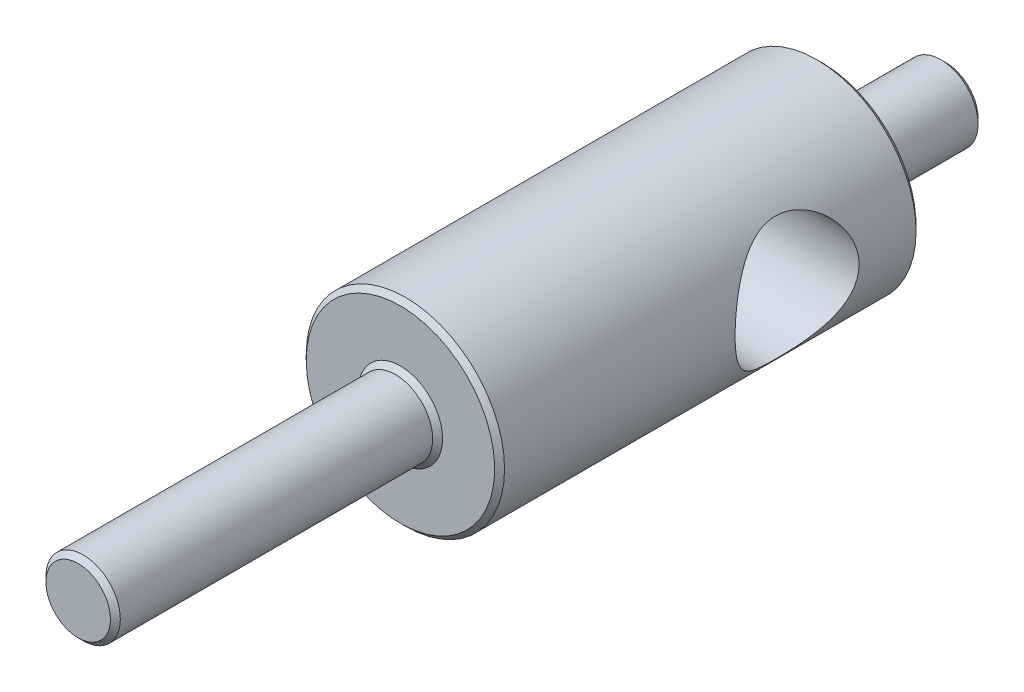
SolidWorks part; units mm, degrees
ref_plane "Front Plane" through (0, 0, 0) normal (0, 0, 1) x (1, 0, 0)
ref_plane "Top Plane" through (0, 0, 0) normal (0, 1, 0) x (1, 0, 0)
ref_plane "Right Plane" through (0, 0, 0) normal (1, 0, 0) x (0, 0, -1)
sketch "Sketch1" plane through (0, 0, 0) normal (0, 0, 1) x (1, 0, 0)
  circle A0 centre (0, 0) radius 1.5
  dimension "D1" = 3
extrude "Boss-Extrude1" add sketch "Sketch1" against normal blind 13
sketch "Sketch2" plane through (0, 0, -13) normal (0, 0, -1) x (-1, 0, 0)
  circle A0 centre (0, 0) radius 4
  dimension "D1" = 8
extrude "Boss-Extrude2" add sketch "Sketch2" along normal blind 17
sketch "Sketch3" plane through (0, 0, -30) normal (0, 0, -1) x (-1, 0, 0)
  circle A0 centre (0, 0) radius 1.5
  dimension "D1" = 3
extrude "Boss-Extrude3" add sketch "Sketch3" along normal blind 5
sketch "Sketch4" plane through (0, 0, 0) normal (1, 0, 0) x (0, 0, -1)
  line L0 (30, -4) -> (30, 4) construction
  circle A0 centre (25, 0) radius 2.5
  dimension "D1" = 5
  dimension "D2" = 5
extrude "Cut-Extrude1" cut sketch "Sketch4" against normal through all both and the other way through all
chamfer "Chamfer1" distance 0.2 angle 45 6 edges at (-1.5, 0, -30) (-1.5, 0, -35) (-4, 0, -30) (1.5, 0, -13) (-4, 0, -13) (1.5, 0, 0)
